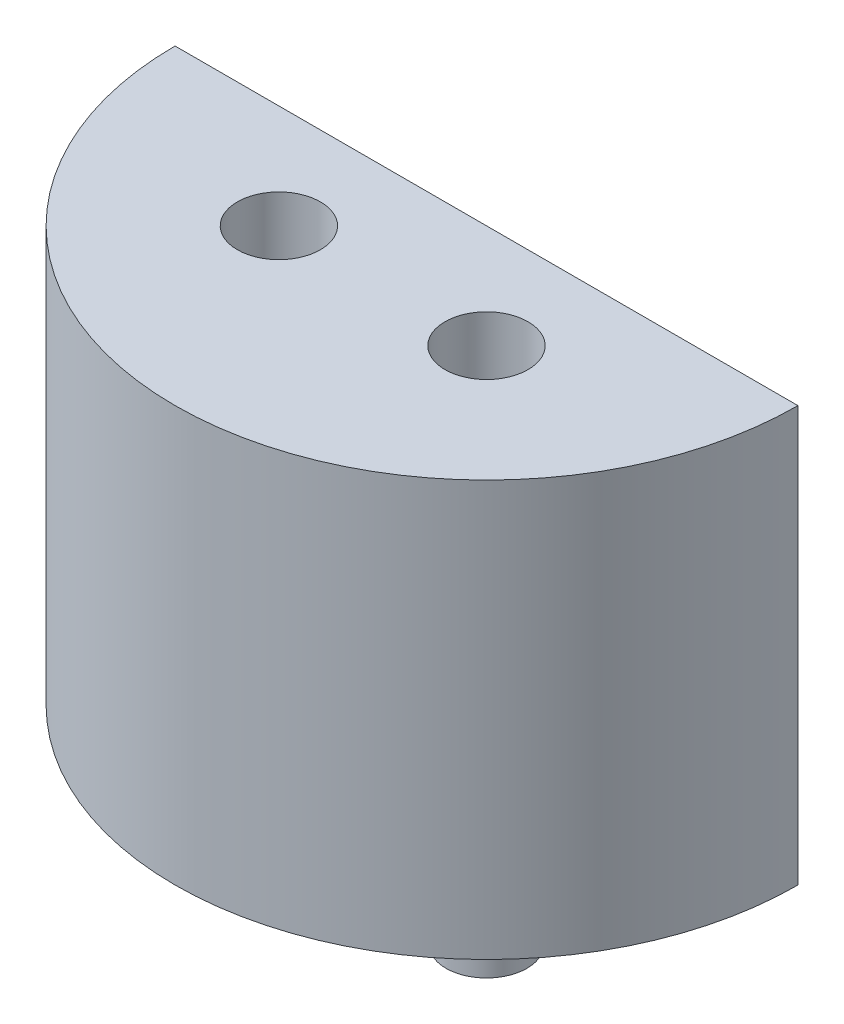
SolidWorks part; units mm, degrees
ref_plane "前视基准面" through (0, 0, 0) normal (0, 0, 1) x (1, 0, 0)
ref_plane "上视基准面" through (0, 0, 0) normal (0, 1, 0) x (1, 0, 0)
ref_plane "右视基准面" through (0, 0, 0) normal (1, 0, 0) x (0, 0, -1)
sketch "草图1" plane through (0, 0, 0) normal (0, 1, 0) x (1, 0, 0)
  line L0 (-15, 0) -> (15, 0)
  arc A0 (-15, 0) -> (15, 0) centre (0, 0) ccw
  dimension "D1" = 30
extrude "凸台-拉伸1" add sketch "草图1" along normal blind 20
sketch "草图2" plane through (0, 20, 0) normal (0, 1, 0) x (1, 0, 0)
  line L0 (0, 0) -> (0, -15.9646) construction
  line L1 (15, 0) -> (-15, 0) construction
  circle A0 centre (-5, -5) radius 2
  circle A1 centre (5, -5) radius 2
  point P9 (-4.0894, -1.8276)
  dimension "D1" = 4
  dimension "D2" = 10
  dimension "D3" = 5
extrude "切除-拉伸1" cut sketch "草图2" against normal blind 6
sketch "草图3" plane through (0, 0, 0) normal (0, -1, 0) x (1, 0, 0)
  circle A0 centre (-5, 5) radius 2 construction
  circle A1 centre (5, 5) radius 2 construction
  circle A2 centre (-5, 5) radius 2 construction
  circle A3 centre (5, 5) radius 2 construction
  circle A4 centre (5, 5) radius 1.95
  circle A5 centre (-5, 5) radius 1.95
  dimension "D1" = 3.9
  dimension "D2" = 3.9
extrude "凸台-拉伸2" add sketch "草图3" along normal blind 5
